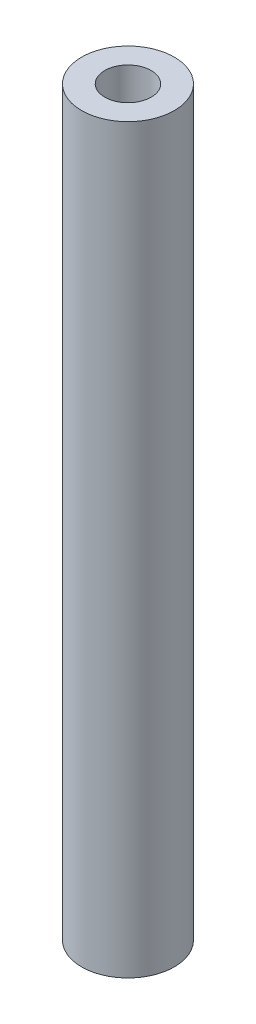
SolidWorks part; units mm, degrees
material "1060 合金"
ref_plane "前视基准面" through (0, 0, 0) normal (0, 0, 1) x (1, 0, 0)
ref_plane "上视基准面" through (0, 0, 0) normal (0, 1, 0) x (1, 0, 0)
ref_plane "右视基准面" through (0, 0, 0) normal (1, 0, 0) x (0, 0, -1)
sketch "草图1" plane through (0, 0, 0) normal (0, 1, 0) x (1, 0, 0)
  circle A0 centre (0, 0) radius 2.5
  circle A1 centre (0, 0) radius 1.25
  dimension "D1" = 5
  dimension "D2" = 2.5
extrude "凸台-拉伸1" add sketch "草图1" along normal blind 40
